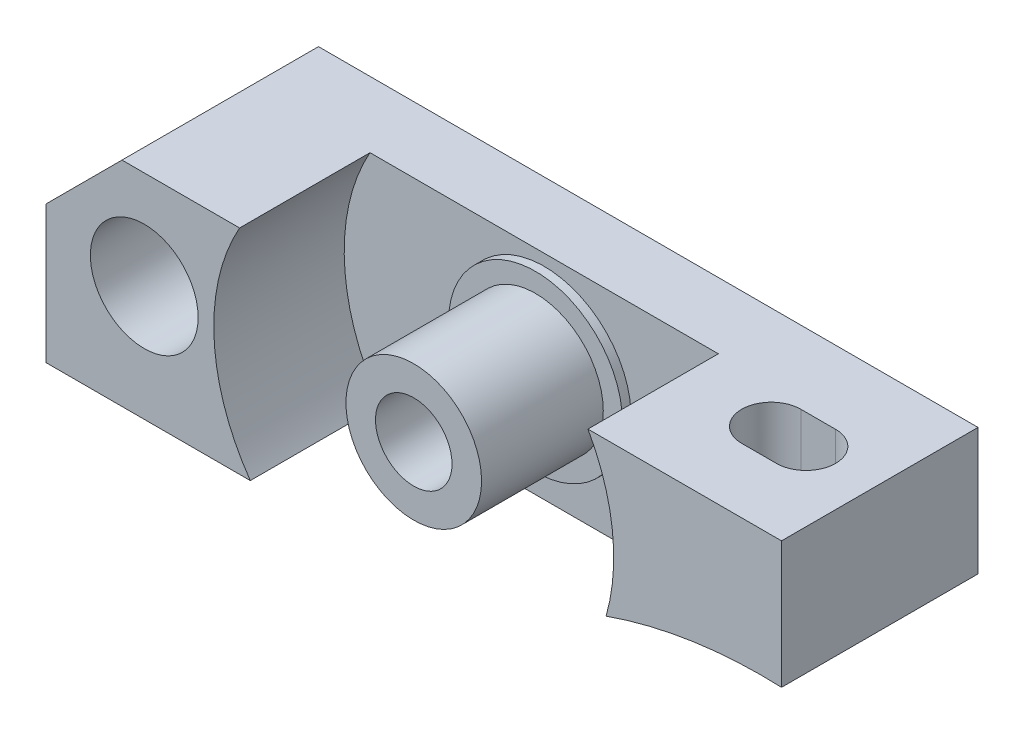
SolidWorks part; units mm, degrees
ref_plane "Piano frontale" through (0, 0, 0) normal (0, 0, 1) x (1, 0, 0)
ref_plane "Piano superiore" through (0, 0, 0) normal (0, 1, 0) x (1, 0, 0)
ref_plane "Piano destro" through (0, 0, 0) normal (1, 0, 0) x (0, 0, -1)
sketch "Schizzo1" plane through (0, 0, 0) normal (0, 0, 1) x (1, 0, 0)
  line L0 (-21.15, 1.7675) -> (-16.78, 6.1375)
  line L1 (-21.15, -6.1375) -> (21.15, -6.1375)
  line L2 (-21.15, -6.1375) -> (-21.15, 1.7675)
  line L3 (-16.78, 6.1375) -> (21.15, 6.1375)
  line L4 (21.15, -6.1375) -> (21.15, 6.1375)
  line L5 (-21.15, -6.1375) -> (21.15, 6.1375) construction
  line L6 (-21.15, 6.1375) -> (21.15, -6.1375) construction
  circle A0 centre (-15.5, 0.4875) radius 1.725
  point P0 (0, 0)
  dimension "D5" = 3.45
  dimension "D1" = 12.275
  dimension "D2" = 42.3
  dimension "D6" = 5.65
  dimension "D7" = 5.65
extrude "Estrusione-Estrusione1" add sketch "Schizzo1" along normal blind 3.8
sketch "Schizzo2" plane through (0, 0, 3.8) normal (0, 0, 1) x (1, 0, 0)
  line L0 (-15.5, 0.4875) -> (0, 0.4875) construction
  line L1 (-10.0164, 6.1375) -> (-16.78, 6.1375)
  line L2 (9.4, -6.1375) -> (21.15, -6.1375)
  line L6 (-21.15, 1.7675) -> (-21.15, -6.1375)
  line L7 (-21.15, -6.1375) -> (21.15, -6.1375)
  line L8 (21.15, -6.1375) -> (21.15, 6.1375)
  line L9 (21.15, 6.1375) -> (-16.78, 6.1375)
  line L10 (-16.78, 6.1375) -> (-21.15, 1.7675)
  line L11 (-21.15, 1.7675) -> (-21.15, -6.1375)
  line L12 (-21.15, -6.1375) -> (-9.4, -6.1375)
  line L13 (21.15, -6.1375) -> (21.15, 6.1375)
  line L14 (21.15, 6.1375) -> (10.0164, 6.1375)
  line L15 (-16.78, 6.1375) -> (-21.15, 1.7675)
  circle A0 centre (-15.5, 0.4875) radius 1.725 construction
  circle A1 centre (-15.5, 0.4875) radius 1.725
  arc A2 (-10.0164, 6.1375) -> (-9.4, -6.1375) centre (0, 0.4875) ccw
  arc A3 (9.4, -6.1375) -> (10.0164, 6.1375) centre (0, 0.4875) ccw
  dimension "D1" = 23
  dimension "D2" = 15.5
  dimension "D3" = 0
extrude "Estrusione-Estrusione2" add sketch "Schizzo2" along normal blind 7.5
sketch "Schizzo4" plane through (0, 0, 11.3) normal (0, 0, 1) x (1, 0, 0)
  circle A0 centre (-15.5, 0.4875) radius 1.725 construction
  circle A1 centre (-15.5, 0.4875) radius 1.725 construction
  circle A2 centre (-15.5, 0.4875) radius 3.1
  dimension "D1" = 6.2
extrude "Taglio-Estrusione1" cut sketch "Schizzo4" against normal blind 5.65
sketch "Schizzo5" plane through (0, 0, 3.8) normal (0, 0, 1) x (1, 0, 0)
  arc A0 (9.4, -6.1375) -> (10.0164, 6.1375) centre (0, 0.4875) ccw construction
  arc A1 (9.4, -6.1375) -> (10.0164, 6.1375) centre (0, 0.4875) ccw construction
  circle A2 centre (0, 0.4875) radius 5
  dimension "D1" = 10
extrude "Estrusione-Estrusione3" add sketch "Schizzo5" along normal blind 0.5
sketch "Schizzo6" plane through (0, 0, 4.3) normal (0, 0, 1) x (1, 0, 0)
  circle A0 centre (0, 0.4875) radius 5 construction
  circle A1 centre (0, 0.4875) radius 5 construction
  circle A2 centre (0, 0.4875) radius 3.9
  dimension "D1" = 7.8
extrude "Estrusione-Estrusione4" add sketch "Schizzo6" along normal blind 7 contours A2
sketch "Schizzo7" plane through (0, 0, 11.3) normal (0, 0, 1) x (1, 0, 0)
  circle A0 centre (0, 0.4875) radius 3.9 construction
  circle A1 centre (0, 0.4875) radius 3.9 construction
  circle A2 centre (0, 0.4875) radius 2.2
  dimension "D1" = 4.4
extrude "Taglio-Estrusione2" cut sketch "Schizzo7" against normal through all
sketch "Schizzo8" plane through (0, 0, 11.3) normal (0, 0, 1) x (1, 0, 0)
  line L0 (11.0616, -2.6575) -> (11.0616, -6.1375) construction
  line L1 (9.4, -6.1375) -> (21.15, -6.1375) construction
  line L2 (21.15, -6.1375) -> (21.15, -1.1616)
  line L3 (21.15, -6.1375) -> (21.15, 6.1375) construction
  line L4 (21.15, -6.1375) -> (4.3414, -6.1375)
  arc A0 (9.4, -6.1375) -> (10.0164, 6.1375) centre (0, 0.4875) ccw construction
  arc A1 (21.15, -1.1616) -> (4.3414, -6.1375) centre (19.9948, -28.1369) ccw
  dimension "D3" = 27
  dimension "D1" = 3.48
  dimension "D2" = 4.9759
extrude "Taglio-Estrusione3" cut sketch "Schizzo8" against normal through all
sketch "Schizzo9" plane through (0, 6.1375, 0) normal (0, 1, 0) x (1, 0, 0)
  line L0 (17.15, -5.89) -> (15.15, -5.89) construction
  line L1 (17.15, -7.59) -> (15.15, -7.59)
  line L2 (17.15, -4.19) -> (15.15, -4.19)
  line L3 (21.15, -11.3) -> (21.15, 0) construction
  line L4 (21.15, 0) -> (-16.78, 0) construction
  arc A0 (17.15, -7.59) -> (17.15, -4.19) centre (17.15, -5.89) ccw
  arc A1 (15.15, -4.19) -> (15.15, -7.59) centre (15.15, -5.89) ccw
  point P2 (16.15, -5.89)
  dimension "D1" = 3.4
  dimension "D2" = 4
  dimension "D3" = 2
  dimension "D4" = 5.89
extrude "Taglio-Estrusione4" cut sketch "Schizzo9" against normal through all
